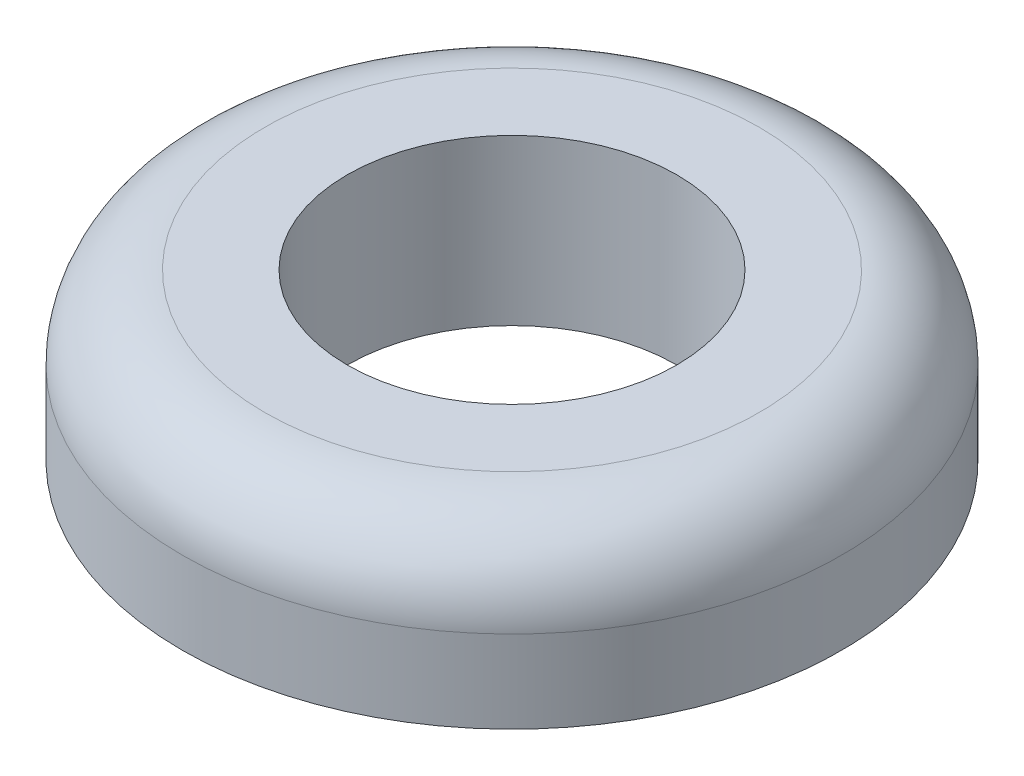
SolidWorks part; units mm, degrees
material "AISI 4340 Steel, annealed"
ref_plane "Front" through (0, 0, 0) normal (0, 0, 1) x (1, 0, 0)
ref_plane "Top" through (0, 0, 0) normal (0, 1, 0) x (1, 0, 0)
ref_plane "Right" through (0, 0, 0) normal (1, 0, 0) x (0, 0, -1)
sketch "Sketch1" plane through (0, 0, 0) normal (0, 1, 0) x (1, 0, 0)
  circle A0 centre (0, 0) radius 3.175
  circle A1 centre (0, 0) radius 6.35
  point P4 (0, 6.35)
  dimension "D1" = 6.35
  dimension "D2" = 12.7
extrude "Boss-Extrude1" add sketch "Sketch1" along normal blind 3.175
fillet "Fillet1" radius 1.5875 1 edges at (0, 3.175, 6.35)
